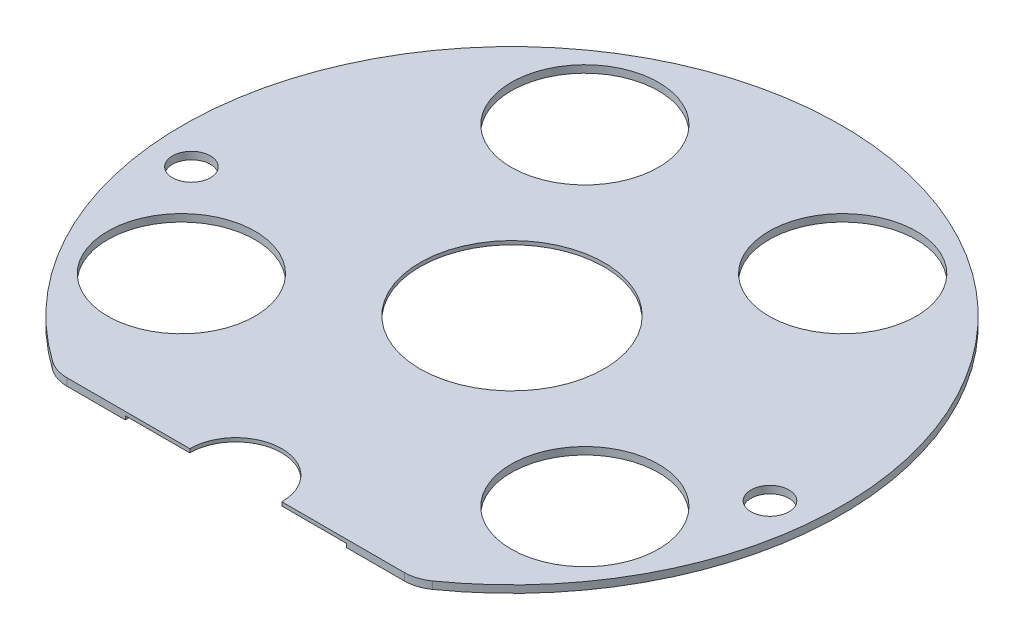
SolidWorks part; units mm, degrees
material "6063-T6"
ref_plane "Front Plane" through (0, 0, 0) normal (0, 0, 1) x (1, 0, 0)
ref_plane "Top Plane" through (0, 0, 0) normal (0, 1, 0) x (1, 0, 0)
ref_plane "Right Plane" through (0, 0, 0) normal (1, 0, 0) x (0, 0, -1)
sketch "Sketch1" plane through (0, 0, 0) normal (0, 1, 0) x (1, 0, 0)
  line L0 (0, 89.5) -> (0, -75) construction
  line L2 (-89.5, 0) -> (89.5, 0) construction
  line L3 (-48.839, -75) -> (48.839, -75)
  arc A0 (48.839, -75) -> (-48.839, -75) centre (0, 0) ccw
  dimension "D1" = 179
  dimension "D2" = 75
extrude "Boss-Extrude1" add sketch "Sketch1" against normal blind 2
sketch "Sketch9" plane through (0, 0, 0) normal (0, 1, 0) x (1, 0, 0)
  line L0 (0, 89.5) -> (0, -75) construction
  line L1 (48.839, -75) -> (-48.839, -75) construction
  line L2 (78.5412, -8.5017) -> (-78.5412, -8.5017) construction
  arc A12 (48.839, -75) -> (-48.839, -75) centre (0, 0) ccw construction
  circle A13 centre (78.5412, -8.5017) radius 5.15
  circle A15 centre (-78.5412, -8.5017) radius 5.15
  point P8 (0, -8.5017)
  dimension "D3" = 10.3
  dimension "D4" = 10.3
  dimension "D2" = 66.4983
  dimension "D1" = 157.0824
extrude "Cut-Extrude3" cut sketch "Sketch9" against normal through all
sketch "Vision Pattern" plane through (0, 0, 0) normal (0, 1, 0) x (1, 0, 0)
  line L0 (64.8074, -55) -> (-64.8074, -55) construction
  line L1 (0, 0) -> (0, -55) construction
  circle A0 centre (0, 0) radius 85 construction
  circle A1 centre (0, 0) radius 25
  circle A2 centre (54.7723, -35) radius 20
  circle A3 centre (-54.7723, -35) radius 20
  circle A4 centre (35, 54.7723) radius 20
  circle A5 centre (-35, 54.7723) radius 20
  circle A6 centre (0, 0) radius 65 construction
  dimension "D1" = 170
  dimension "D3" = 50
  dimension "D4" = 40
  dimension "D2" = 55
  dimension "D5" = 35
  dimension "D8" = 65
  dimension "D6" = 35
  dimension "D7" = 35
extrude "Cut-Extrude4" cut sketch "Vision Pattern" against normal through all
fillet "Fillet1" radius 10 2 edges at (-48.839, -1, 75) (48.839, -1, 75)
ref_plane "Plane2" through (0, 0, -97) normal (0, 0, 1) x (1, 0, 0)
ref_plane "Plane3" through (0, 0, 5) normal (0, 0, 1) x (1, 0, 0)
sketch "Sketch18" plane through (0, 0, 5) normal (0, 0, 1) x (1, 0, 0)
  line L0 (63.1128, -3.45) -> (66.8872, -3.45)
  line L1 (66.8872, -3.45) -> (66.05, -2)
  line L2 (66.05, -2) -> (63.95, -2)
  line L3 (63.95, -2) -> (63.1128, -3.45)
  line L4 (-45.7739, -2) -> (45.7739, -2) construction
  line L6 (-45.7739, -2) -> (45.7739, -2) construction
  point P8 (0, -2)
  point P9 (65, -2)
  dimension "D1" = 60
  dimension "D2" = 60
  dimension "D3" = 1.45
  dimension "D4" = 2.1
  dimension "D5" = 65
extrude "Boss-Extrude4" add sketch "Sketch18" against normal blind 50
mirror "Mirror2" about plane through (0, 0, 0) normal (1, 0, 0) of "Boss-Extrude4"
sketch "Sketch12" plane through (0, -2, 0) normal (0, -1, 0) x (1, 0, 0)
  line L0 (-45.7739, 75) -> (45.7739, 75) construction
  line L1 (-30, 75) -> (30, 75)
  line L2 (-30, 75) -> (-30, -30)
  line L3 (-30, -30) -> (30, -30)
  line L4 (30, 75) -> (30, -30)
  point P6 (0, -30)
  dimension "D1" = 60
  dimension "D2" = 30
extrude "Cut-Extrude5" cut sketch "Sketch12" against normal blind 1
sketch "Sketch16" plane through (0, 0, 0) normal (0, 1, 0) x (1, 0, 0)
  line L0 (-45.7739, -75) -> (45.7739, -75) construction
  circle A0 centre (0, -75) radius 12.5
  dimension "D1" = 25
extrude "Cut-Extrude9" cut sketch "Sketch16" against normal blind 20
sketch "Sketch17" plane through (0, -1, 0) normal (0, -1, 0) x (1, 0, 0)
  line L2 (-30, 75) -> (21.25, 75) construction
  line L3 (30, 75) -> (12.5, 75) construction
  line L4 (-30, 75) -> (-30, -30) construction
  circle A1 centre (-20, 72.05) radius 0.75
  dimension "D1" = 10
  dimension "D3" = 1.5
  dimension "D4" = 2.95
extrude "Boss-Extrude3" add sketch "Sketch17" along normal blind 0.425 contours A1
mirror "Mirror1" about plane through (0, 0, 0) normal (1, 0, 0) of "Boss-Extrude3"
fillet "Fillet2" radius 0.4 2 edges at (20, -1.425, 71.3) (-20, -1.425, 71.3)
sketch "Sketch19" plane through (0, -3.45, 0) normal (0, -1, 0) x (1, 0, 0)
  line L1 (95.4806, 15.0963) -> (57.8669, 15.0963)
  line L2 (95.4806, 15.0963) -> (95.4806, -73.6368)
  line L3 (95.4806, -73.6368) -> (57.8669, -73.6368)
  line L4 (57.8669, 15.0963) -> (57.8669, -73.6368)
extrude "Test-Print" [suppressed] cut sketch "Sketch19" against normal through all both and the other way through all flip side to cut
equation "\"D4@Sketch9\"=\"D3@Sketch9\""
equation "\"D1@Vision Pattern\" = 85 * 2"
equation "\"D7@Vision Pattern\"=\"D6@Vision Pattern\""
equation "\"20Gauge\"= .911"
